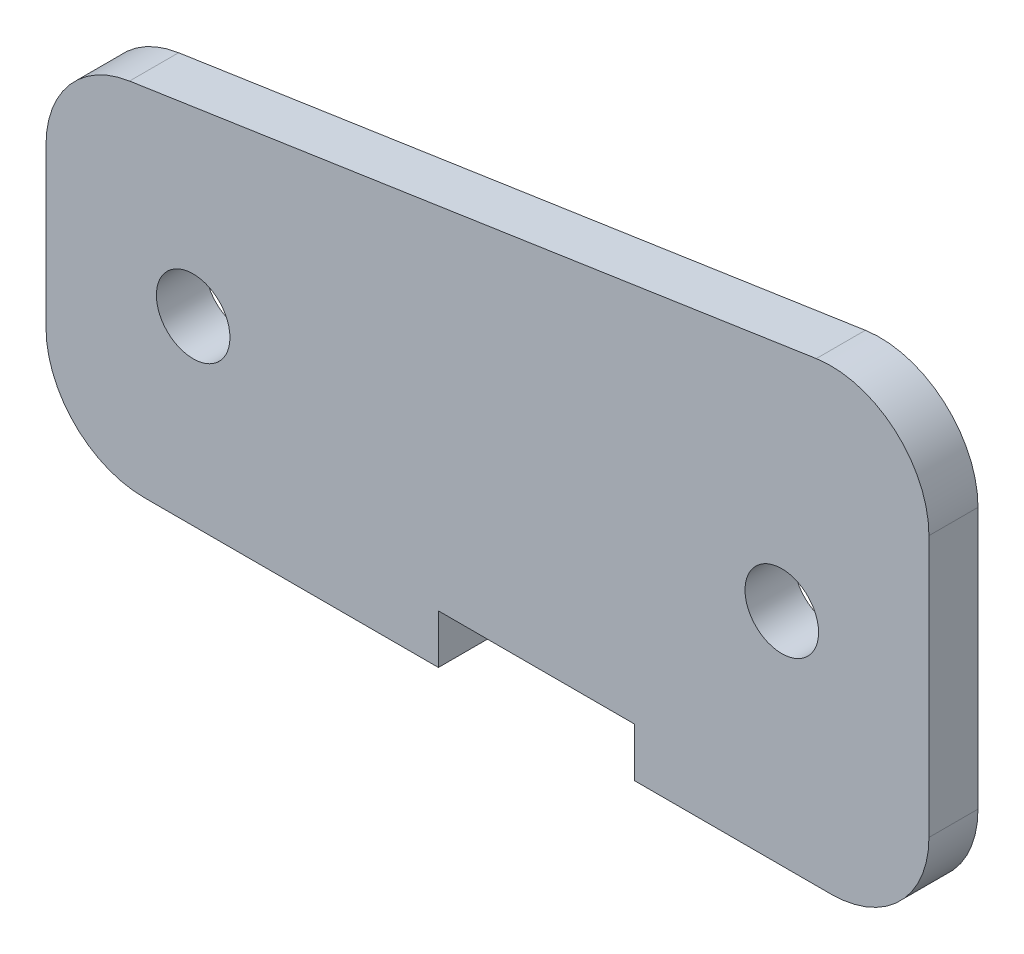
SolidWorks part; units mm, degrees
ref_plane "Front Plane" through (0, 0, 0) normal (0, 0, 1) x (1, 0, 0)
ref_plane "Top Plane" through (0, 0, 0) normal (0, 1, 0) x (1, 0, 0)
ref_plane "Right Plane" through (0, 0, 0) normal (1, 0, 0) x (0, 0, -1)
sketch "Sketch1" plane through (0, 0, 0) normal (0, 0, 1) x (1, 0, 0)
  line L1 (-270.5925, 23.5454) -> (-226.1425, 30.2129)
  line L2 (-250.6005, 0.6679) -> (-237.9005, 0.6679)
  line L3 (-250.6005, 0.6679) -> (-250.6005, 3.8429)
  line L4 (-250.6005, 3.8429) -> (-237.9005, 3.8429)
  line L5 (-237.9005, 0.6679) -> (-237.9005, 3.8429)
  line L9 (-228.3755, 0) -> (-228.3755, 29.8779)
  line L10 (-266.4755, 0.6679) -> (-266.4755, 24.1629)
  line L13 (-218.8505, 23.9331) -> (-218.8505, 7.0179)
  line L14 (-276.0005, 17.2656) -> (-276.0005, 7.0179)
  line L16 (-225.2005, 0.6679) -> (-269.6505, 0.6679)
  circle A0 centre (-266.4755, 12.4154) radius 2.3813
  circle A1 centre (-228.3755, 14.939) radius 2.3813
  arc A2 (-218.8505, 23.9331) -> (-226.1425, 30.2129) centre (-225.2005, 23.9331) ccw
  arc A3 (-218.8505, 7.0179) -> (-225.2005, 0.6679) centre (-225.2005, 7.0179) cw
  arc A4 (-276.0005, 7.0179) -> (-269.6505, 0.6679) centre (-269.6505, 7.0179) ccw
  arc A5 (-276.0005, 17.2656) -> (-270.5925, 23.5454) centre (-269.6505, 17.2656) cw
  point P11 (-218.8505, 31.3067)
  point P14 (-218.8505, 0.6679)
  point P22 (-276.0005, 0.6679)
  point P27 (-276.0005, 22.7342)
  dimension "D1" = 4.7625
  dimension "D2" = 4.7625
  dimension "D11" = 6.35
  dimension "D3" = 12.7
  dimension "D4" = 9.525
  dimension "D6" = 30.6388
  dimension "D7" = 9.525
  dimension "D8" = 9.525
  dimension "D5" = 3.175
  dimension "D9" = 22.0663
  dimension "D10" = 57.15
extrude "Boss-Extrude1" add sketch "Sketch1" along normal blind 3.175 contours A5 L14 A4 L16 L10 A0 L1 | A1 L9 L1 L10 A0 L16 L3 L4 L5 | A3 L13 A2 L1 L9 A1 L16
